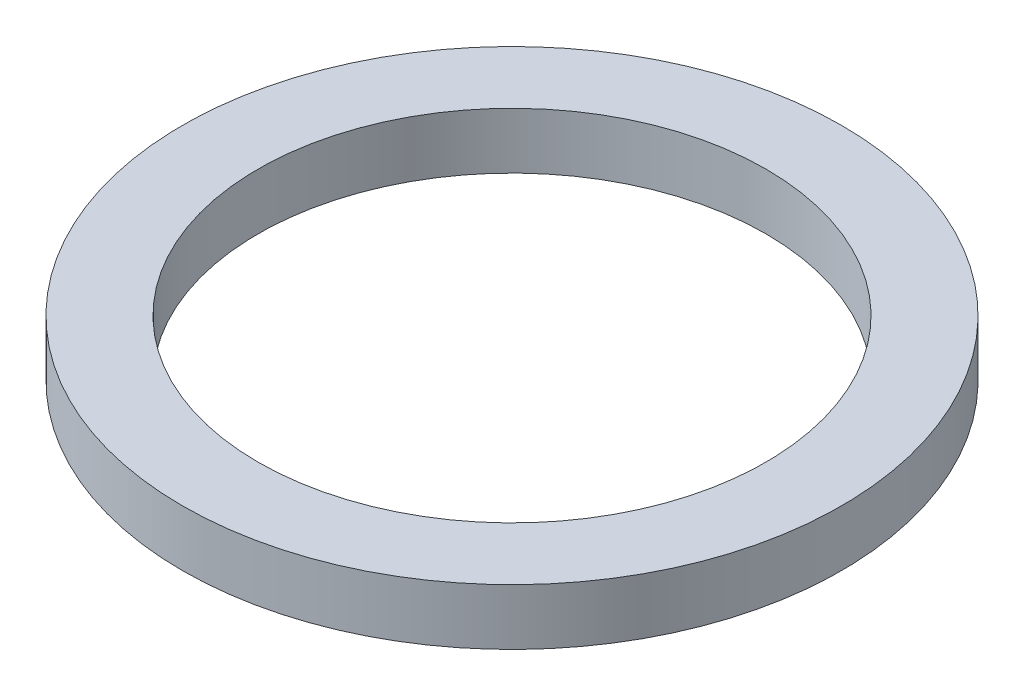
SolidWorks part; units mm, degrees
ref_plane "Front Plane" through (0, 0, 0) normal (0, 0, 1) x (1, 0, 0)
ref_plane "Top Plane" through (0, 0, 0) normal (0, 1, 0) x (1, 0, 0)
ref_plane "Right Plane" through (0, 0, 0) normal (1, 0, 0) x (0, 0, -1)
sketch "Sketch1" plane through (0, 0, 0) normal (0, 1, 0) x (1, 0, 0)
  circle A0 centre (0, 0) radius 28.7274
  circle A1 centre (0, 0) radius 37.2872
  dimension "D1" = 57.4548
  dimension "D2" = 74.5744
extrude "Boss-Extrude1" add sketch "Sketch1" along normal blind 6.35
